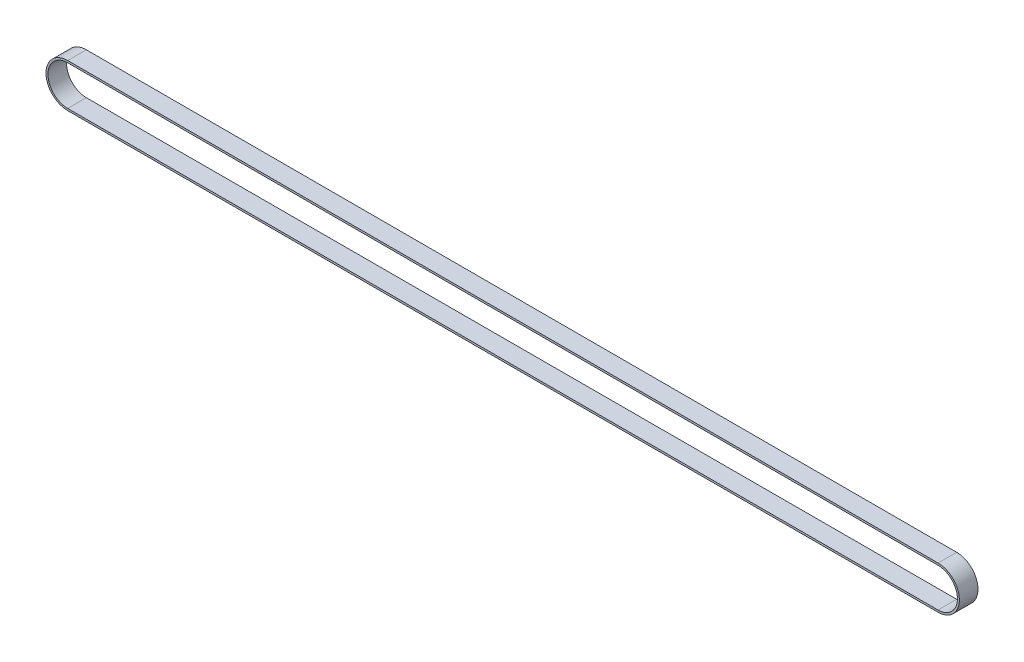
SolidWorks part; units mm, degrees
material "NEOPRENO"
ref_plane "Alzado" through (0, 0, 0) normal (0, 0, 1) x (1, 0, 0)
ref_plane "Planta" through (0, 0, 0) normal (0, 1, 0) x (1, 0, 0)
ref_plane "Vista lateral" through (0, 0, 0) normal (1, 0, 0) x (0, 0, -1)
sketch "Croquis1" plane through (0, 0, 0) normal (0, 0, 1) x (1, 0, 0)
  line L0 (-24.7527, 6.3565) -> (255.6472, 6.3565)
  line L1 (255.6472, 6.9865) -> (-24.7527, 6.9865)
  line L2 (-24.7527, -6.3755) -> (255.6472, -6.1235)
  line L3 (-24.7527, -7.0055) -> (255.6534, -6.7535)
  arc A0 (-24.7527, 6.3565) -> (-24.7527, -6.3755) centre (-24.7527, -0.0095) ccw
  arc A1 (255.6472, -6.1235) -> (255.6472, 6.3565) centre (255.6472, 0.1165) ccw
  arc A2 (-24.7527, 6.9865) -> (-24.7527, -7.0055) centre (-24.7527, -0.0095) ccw
  arc A3 (255.6534, -6.7535) -> (255.6472, 6.9865) centre (255.6472, 0.1165) ccw
  dimension "D1" = 12.732
  dimension "D2" = 12.48
  dimension "D3" = 0.63
  dimension "D4" = 280.4
extrude "Saliente-Extruir1" add sketch "Croquis1" along normal blind 6
